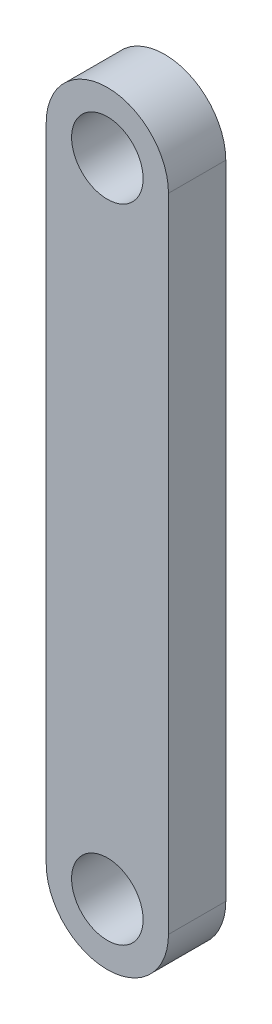
SolidWorks part; units mm, degrees
material "Titanium"
ref_plane "Front Plane" through (0, 0, 0) normal (0, 0, 1) x (1, 0, 0)
ref_plane "Top Plane" through (0, 0, 0) normal (0, 1, 0) x (1, 0, 0)
ref_plane "Right Plane" through (0, 0, 0) normal (1, 0, 0) x (0, 0, -1)
sketch "Sketch1" plane through (0, 0, 0) normal (0, 0, 1) x (1, 0, 0)
  line L3 (-3.2, 33.6) -> (-3.2, 0)
  line L4 (1.65, 0) -> (-1.65, 0) construction
  line L5 (3.2, 33.6) -> (3.2, 0)
  circle A2 centre (0, 0) radius 1.872
  circle A3 centre (0, 33.6) radius 1.872
  arc A4 (3.2, 33.6) -> (-3.2, 33.6) centre (0, 33.6) ccw
  arc A5 (-3.2, 0) -> (3.2, 0) centre (0, 0) ccw
  dimension "D1" = 6.4
  dimension "D2" = 3.744
  dimension "D3" = 33.6
extrude "Boss-Extrude1" add sketch "Sketch1" along normal blind 3
equation "\"bScale\"= 8"
equation "\"lScale\"= 8"
equation "\"D1@Sketch1\"=.8*\"bScale\""
equation "\"D2@Sketch1\"=0.468 * \"bScale\""
equation "\"D3@Sketch1\"=4.2*\"lScale\""
